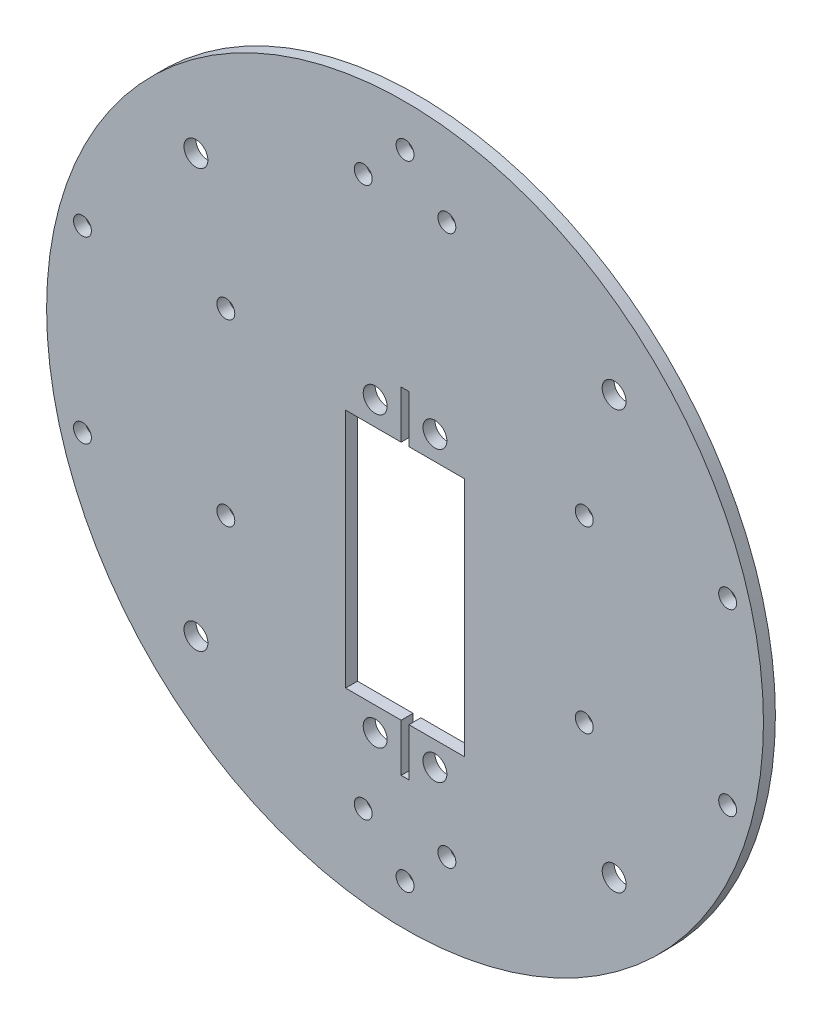
SolidWorks part; units mm, degrees
material "普通碳钢"
ref_plane "前视" through (0, 0, 0) normal (0, 0, 1) x (1, 0, 0)
ref_plane "上视" through (0, 0, 0) normal (0, 1, 0) x (1, 0, 0)
ref_plane "右视" through (0, 0, 0) normal (1, 0, 0) x (0, 0, -1)
sketch "草图2" plane through (0, 0, 0) normal (0, 0, 1) x (1, 0, 0)
  line L0 (1.0372, -12.2442) -> (1.0372, -20.2442)
  line L1 (2.3372, -20.2442) -> (2.3372, -12.2442)
  line L2 (2.3372, -12.2442) -> (11.6467, -12.2442)
  line L3 (11.6467, -12.2442) -> (11.6467, 28.0558)
  line L4 (11.6467, 28.0558) -> (2.3372, 28.0558)
  line L5 (2.3372, 28.0558) -> (2.3372, 36.0558)
  line L6 (1.0372, 36.0558) -> (1.0372, 28.0558)
  line L7 (1.0372, 28.0558) -> (-8.2722, 28.0558)
  line L8 (-8.2722, 28.0558) -> (-8.2722, -12.2442)
  line L9 (-8.2722, -12.2442) -> (1.0372, -12.2442)
  line L10 (14.1872, 13.7581) -> (14.1872, 7.7581)
  line L11 (17.1872, 7.7581) -> (17.1872, 13.7581)
  line L12 (-10.8128, 7.7581) -> (-10.8128, 13.7581)
  line L13 (-13.8128, 13.7581) -> (-13.8128, 7.7581)
  line L14 (-10.8128, 21.7581) -> (-10.8128, 27.7581)
  line L15 (-13.8128, 27.7581) -> (-13.8128, 21.7581)
  line L16 (17.1872, 21.7581) -> (17.1872, 27.7581)
  line L17 (14.1872, 27.7581) -> (14.1872, 21.7581)
  line L18 (15.6872, -29.7419) -> (22.6872, -29.7419)
  line L19 (22.6872, -26.7419) -> (15.6872, -26.7419)
  line L20 (-19.3128, -29.7419) -> (-12.3128, -29.7419)
  line L21 (-12.3128, -26.7419) -> (-19.3128, -26.7419)
  line L22 (-19.3128, 62.2581) -> (-12.3128, 62.2581)
  line L23 (-12.3128, 65.2581) -> (-19.3128, 65.2581)
  line L24 (15.6872, 62.2581) -> (22.6872, 62.2581)
  line L25 (22.6872, 65.2581) -> (15.6872, 65.2581)
  line L26 (-19.3128, 37.2581) -> (-12.3128, 37.2581)
  line L27 (-12.3128, 40.2581) -> (-19.3128, 40.2581)
  line L28 (15.6872, 37.2581) -> (22.6872, 37.2581)
  line L29 (22.6872, 40.2581) -> (15.6872, 40.2581)
  line L30 (49.6872, 16.2581) -> (55.6872, 16.2581)
  line L31 (55.6872, 19.2581) -> (49.6872, 19.2581)
  line L32 (-52.3128, 16.2581) -> (-46.3128, 16.2581)
  line L33 (-46.3128, 19.2581) -> (-52.3128, 19.2581)
  line L34 (-5.3128, 62.2581) -> (8.6872, 62.2581)
  line L35 (8.6872, 65.2581) -> (-5.3128, 65.2581)
  line L36 (1.0372, 36.0558) -> (2.3372, 36.0558)
  line L37 (2.3372, -20.2442) -> (1.0372, -20.2442)
  circle A0 centre (1.6855, 17.7599) radius 60
  circle A1 centre (-3.3128, 32.0508) radius 2
  circle A2 centre (6.6872, -16.2492) radius 2
  circle A3 centre (-3.3128, -16.2492) radius 2
  circle A4 centre (-28.3128, 32.7581) radius 1.5
  circle A5 centre (-52.3128, 32.7581) radius 1.5
  circle A6 centre (-28.3128, 2.7581) radius 1.5
  circle A7 centre (-52.3128, 2.7581) radius 1.5
  circle A8 centre (31.6872, 32.7581) radius 1.5
  circle A9 centre (55.6872, 32.7581) radius 1.5
  circle A10 centre (31.6872, 2.7581) radius 1.5
  circle A11 centre (55.6872, 2.7581) radius 1.5
  circle A12 centre (36.689, -17.2365) radius 2
  circle A13 centre (-33.311, -17.2436) radius 2
  circle A14 centre (-33.3181, 52.7564) radius 2
  circle A15 centre (36.6819, 52.7635) radius 2
  circle A16 centre (-12.3128, -3.2419) radius 1.5
  circle A17 centre (15.6872, -3.2419) radius 1.5
  circle A18 centre (42.6872, 24.7581) radius 1.5
  circle A19 centre (42.6872, 10.7581) radius 1.5
  circle A20 centre (35.6872, 17.7581) radius 1.5
  circle A21 centre (-39.3128, 24.7581) radius 1.5
  circle A22 centre (-39.3128, 10.7581) radius 1.5
  circle A23 centre (-32.3128, 17.7581) radius 1.5
  circle A24 centre (1.6872, -35.2419) radius 1.5
  circle A25 centre (6.6872, 32.0508) radius 2
  circle A26 centre (1.6872, -28.2419) radius 3
  circle A27 centre (8.6872, -28.2419) radius 1.5
  circle A28 centre (-5.3128, -28.2419) radius 1.5
  circle A29 centre (49.6872, 10.7581) radius 1.5
  circle A30 centre (42.6872, 17.7581) radius 1.5
  circle A31 centre (49.6872, 24.7581) radius 1.5
  circle A32 centre (-39.3128, 17.7581) radius 1.5
  circle A33 centre (-46.3128, 10.7581) radius 1.5
  circle A34 centre (-46.3128, 24.7581) radius 1.5
  circle A35 centre (1.6872, 70.7581) radius 1.5
  circle A36 centre (1.6872, 56.7581) radius 1.5
  arc A37 (14.1872, 7.7581) -> (17.1872, 7.7581) centre (15.6872, 7.7581) ccw
  arc A38 (17.1872, 13.7581) -> (14.1872, 13.7581) centre (15.6872, 13.7581) ccw
  arc A39 (-13.8128, 7.7581) -> (-10.8128, 7.7581) centre (-12.3128, 7.7581) ccw
  arc A40 (-10.8128, 13.7581) -> (-13.8128, 13.7581) centre (-12.3128, 13.7581) ccw
  arc A41 (-13.8128, 21.7581) -> (-10.8128, 21.7581) centre (-12.3128, 21.7581) ccw
  arc A42 (-10.8128, 27.7581) -> (-13.8128, 27.7581) centre (-12.3128, 27.7581) ccw
  arc A43 (17.1872, 27.7581) -> (14.1872, 27.7581) centre (15.6872, 27.7581) ccw
  arc A44 (14.1872, 21.7581) -> (17.1872, 21.7581) centre (15.6872, 21.7581) ccw
  arc A45 (22.6872, -29.7419) -> (22.6872, -26.7419) centre (22.6872, -28.2419) ccw
  arc A46 (15.6872, -26.7419) -> (15.6872, -29.7419) centre (15.6872, -28.2419) ccw
  arc A47 (-12.3128, -29.7419) -> (-12.3128, -26.7419) centre (-12.3128, -28.2419) ccw
  arc A48 (-19.3128, -26.7419) -> (-19.3128, -29.7419) centre (-19.3128, -28.2419) ccw
  arc A49 (-12.3128, 62.2581) -> (-12.3128, 65.2581) centre (-12.3128, 63.7581) ccw
  arc A50 (-19.3128, 65.2581) -> (-19.3128, 62.2581) centre (-19.3128, 63.7581) ccw
  arc A51 (22.6872, 62.2581) -> (22.6872, 65.2581) centre (22.6872, 63.7581) ccw
  arc A52 (15.6872, 65.2581) -> (15.6872, 62.2581) centre (15.6872, 63.7581) ccw
  arc A53 (-19.3128, 40.2581) -> (-19.3128, 37.2581) centre (-19.3128, 38.7581) ccw
  arc A54 (-12.3128, 37.2581) -> (-12.3128, 40.2581) centre (-12.3128, 38.7581) ccw
  arc A55 (22.6872, 37.2581) -> (22.6872, 40.2581) centre (22.6872, 38.7581) ccw
  arc A56 (15.6872, 40.2581) -> (15.6872, 37.2581) centre (15.6872, 38.7581) ccw
  arc A57 (55.6872, 16.2581) -> (55.6872, 19.2581) centre (55.6872, 17.7581) ccw
  arc A58 (49.6872, 19.2581) -> (49.6872, 16.2581) centre (49.6872, 17.7581) ccw
  arc A59 (-52.3128, 19.2581) -> (-52.3128, 16.2581) centre (-52.3128, 17.7581) ccw
  arc A60 (-46.3128, 16.2581) -> (-46.3128, 19.2581) centre (-46.3128, 17.7581) ccw
  arc A61 (-5.3128, 65.2581) -> (-5.3128, 62.2581) centre (-5.3128, 63.7581) ccw
  arc A62 (8.6872, 62.2581) -> (8.6872, 65.2581) centre (8.6872, 63.7581) ccw
  circle A63 centre (1.6855, 17.7599) radius 49.4975 construction
  dimension "D1" = 3
  dimension "D5" = 70
  dimension "D2" = 70
  dimension "D3" = 70
  dimension "D4" = 70
extrude "凸台-拉伸1" add sketch "草图2" along normal blind 2
sketch "草图3" plane through (0, 0, 2) normal (0, 0, 1) x (1, 0, 0)
  line L1 (21.2985, -8.1421) -> (13.1361, -8.1421)
  line L2 (21.2985, -8.1421) -> (21.2985, 32.3432)
  line L3 (21.2985, 32.3432) -> (13.1361, 32.3432)
  line L4 (13.1361, -8.1421) -> (13.1361, 32.3432)
  line L5 (57.905, 7.0332) -> (30.7652, 7.0332)
  line L6 (57.905, 7.0332) -> (57.905, 28.0558)
  line L7 (57.905, 28.0558) -> (30.7652, 28.0558)
  line L8 (30.7652, 7.0332) -> (30.7652, 28.0558)
  line L9 (26.2311, 36.5257) -> (11.6467, 36.5257)
  line L10 (26.2311, 36.5257) -> (26.2311, 42.576)
  line L11 (26.2311, 42.576) -> (11.6467, 42.576)
  line L12 (11.6467, 36.5257) -> (11.6467, 42.576)
  line L13 (26.2311, 53.7593) -> (-22.6247, 53.7593)
  line L14 (26.2311, 53.7593) -> (26.2311, 66.6516)
  line L15 (26.2311, 66.6516) -> (-22.6247, 66.6516)
  line L16 (-22.6247, 53.7593) -> (-22.6247, 66.6516)
  line L17 (-4.927, 73.215) -> (7.9653, 73.215)
  line L18 (-4.927, 73.215) -> (-4.927, 68.6441)
  line L19 (-4.927, 68.6441) -> (7.9653, 68.6441)
  line L20 (7.9653, 73.215) -> (7.9653, 68.6441)
  line L21 (-9.5656, -6.7447) -> (-18.444, -6.7447)
  line L22 (-9.5656, -6.7447) -> (-9.5656, 32.3432)
  line L23 (-9.5656, 32.3432) -> (-18.444, 32.3432)
  line L24 (-18.444, -6.7447) -> (-18.444, 32.3432)
  line L25 (-7.0509, 35.2928) -> (-26.8491, 35.2928)
  line L26 (-7.0509, 35.2928) -> (-7.0509, 45.6025)
  line L27 (-7.0509, 45.6025) -> (-26.8491, 45.6025)
  line L28 (-26.8491, 35.2928) -> (-26.8491, 45.6025)
  line L29 (-28.6947, 7.9058) -> (-55.3608, 7.9058)
  line L30 (-28.6947, 7.9058) -> (-28.6947, 27.7581)
  line L31 (-28.6947, 27.7581) -> (-55.3608, 27.7581)
  line L32 (-55.3608, 7.9058) -> (-55.3608, 27.7581)
  line L33 (-9.5656, -31.938) -> (-23.352, -31.938)
  line L34 (-9.5656, -31.938) -> (-9.5656, -24.1979)
  line L35 (-9.5656, -24.1979) -> (-23.352, -24.1979)
  line L36 (-23.352, -31.938) -> (-23.352, -24.1979)
  line L37 (26.2311, -31.0898) -> (11.6467, -31.0898)
  line L38 (26.2311, -31.0898) -> (26.2311, -24.1979)
  line L39 (26.2311, -24.1979) -> (11.6467, -24.1979)
  line L40 (11.6467, -31.0898) -> (11.6467, -24.1979)
  line L41 (5.6737, -31.938) -> (-2.2508, -31.938)
  line L42 (5.6737, -31.938) -> (5.6737, -24.1979)
  line L43 (5.6737, -24.1979) -> (-2.2508, -24.1979)
  line L44 (-2.2508, -31.938) -> (-2.2508, -24.1979)
extrude "凸台-拉伸2" add sketch "草图3" against normal blind 2
sketch "草图4" plane through (0, 0, 2) normal (0, 0, 1) x (1, 0, 0)
  line L1 (1.6855, 17.7599) -> (-58.3145, 17.7599) construction
  circle A1 centre (1.6872, -35.2419) radius 1.5
  circle A2 centre (-5.3128, -28.2419) radius 1.5
  circle A3 centre (8.6872, -28.2419) radius 1.5
  circle A4 centre (8.6872, 63.7617) radius 1.5
  circle A5 centre (-5.3128, 63.7617) radius 1.5
  circle A6 centre (1.6872, 70.7617) radius 1.5
extrude "切除-拉伸1" cut sketch "草图4" against normal blind 2
